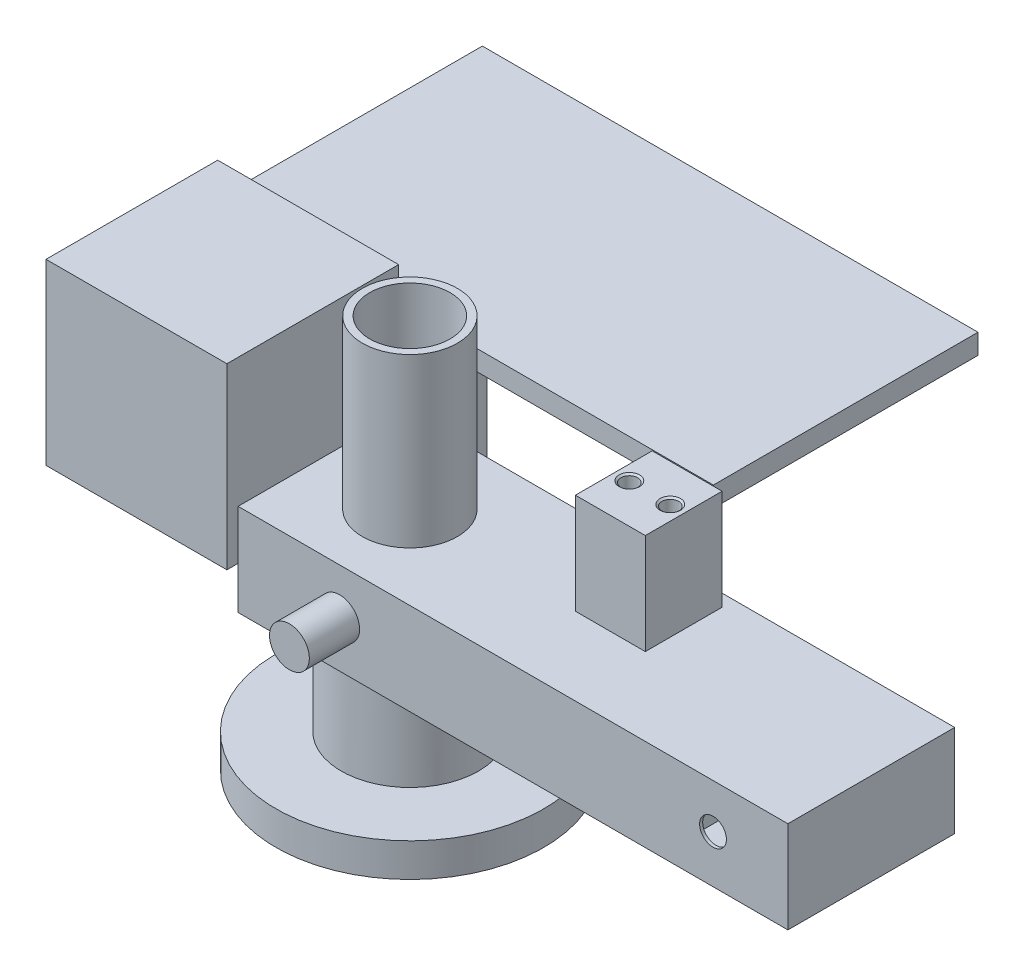
SolidWorks part; units mm, degrees
ref_plane "前基準面" through (0, 0, 0) normal (0, 0, 1) x (1, 0, 0)
ref_plane "上基準面" through (0, 0, 0) normal (0, 1, 0) x (1, 0, 0)
ref_plane "右基準面" through (0, 0, 0) normal (1, 0, 0) x (0, 0, -1)
sketch "草圖1" plane through (0, 0, 0) normal (0, 1, 0) x (1, 0, 0)
  line L1 (-30.3038, 12.448) -> (30.3038, 12.448)
  line L2 (-30.3038, 12.448) -> (-30.3038, -12.448)
  line L3 (-30.3038, -12.448) -> (30.3038, -12.448)
  line L4 (30.3038, 12.448) -> (30.3038, -12.448)
  line L5 (-30.3038, 12.448) -> (30.3038, -12.448) construction
  line L6 (-30.3038, -12.448) -> (30.3038, 12.448) construction
  point P0 (0, 0)
extrude "填料-伸長1" add sketch "草圖1" along normal blind 13.7304
sketch "草圖2" plane through (0, 0, 12.448) normal (0, 0, 1) x (1, 0, 0)
  line L6 (11.75, 12.75) -> (24.25, 12.75)
  line L7 (11.75, 12.75) -> (11.75, 2.25)
  line L8 (11.75, 2.25) -> (24.25, 2.25)
  line L9 (24.25, 12.75) -> (24.25, 2.25)
  line L10 (11.75, 12.75) -> (24.25, 2.25) construction
  line L11 (11.75, 2.25) -> (24.25, 12.75) construction
  point P10 (18, 7.5)
  dimension "D1" = 10.5
  dimension "D2" = 12.5
extrude "除料-伸長1" cut sketch "草圖2" against normal through all
sketch "草圖3" plane through (0, 0, 12.448) normal (0, 0, 1) x (1, 0, 0)
  line L0 (24.25, 2.25) -> (24.25, 12.75) construction
  line L1 (11.75, 12.75) -> (24.25, 12.75)
  line L2 (11.75, 12.75) -> (11.75, 2.25)
  line L3 (11.75, 2.25) -> (24.25, 2.25)
  line L4 (24.25, 12.75) -> (24.25, 2.25)
  line L5 (11.75, 12.75) -> (24.25, 2.25) construction
  line L6 (11.75, 2.25) -> (24.25, 12.75) construction
  line L7 (11.75, 2.25) -> (24.25, 2.25) construction
  point P0 (18, 7.5)
extrude "填料-伸長2" add sketch "草圖3" against normal blind 0.5
sketch "草圖4" plane through (0, 0, 11.948) normal (0, 0, -1) x (-1, 0, 0)
  circle A0 centre (-18, 7.5) radius 2
extrude "除料-伸長2" cut sketch "草圖4" against normal through all
sketch "草圖5" plane through (0, 0, 12.448) normal (0, 0, 1) x (1, 0, 0)
  circle A0 centre (-15.1519, 6.9) radius 2.975
extrude "填料-伸長3" add sketch "草圖5" along normal blind 7.5
sketch "草圖10" plane through (0, 13.7304, 0) normal (0, 1, 0) x (1, 0, 0)
  line L5 (8.4266, 10.6185) -> (18.8582, 10.6185)
  line L6 (8.4266, 10.6185) -> (8.4266, -0.8383)
  line L7 (8.4266, -0.8383) -> (18.8582, -0.8383)
  line L8 (18.8582, 10.6185) -> (18.8582, -0.8383)
  line L9 (8.4266, 10.6185) -> (18.8582, -0.8383) construction
  line L10 (8.4266, -0.8383) -> (18.8582, 10.6185) construction
  point P0 (13.6424, 4.8901)
extrude "填料-伸長4" add sketch "草圖10" along normal blind 15
sketch "草圖14" plane through (0, 0, 12.448) normal (0, 0, 1) x (1, 0, 0)
  circle A0 centre (18, 7.5) radius 2.8505
  circle A1 centre (18, 7.5) radius 2
extrude "填料-伸長5" add sketch "草圖14" along normal blind 1.5
sketch "草圖16" plane through (0, 0, 0) normal (0, -1, 0) x (1, 0, 0)
  circle A0 centre (-17.1174, 0) radius 5.5
  circle A1 centre (-17.1174, 0) radius 7.5
extrude "填料-伸長6" add sketch "草圖16" along normal blind 15
sketch "草圖17" plane through (0, -15, 0) normal (0, -1, 0) x (1, 0, 0)
  circle A0 centre (-17.1174, 0) radius 9.15
  circle A1 centre (-17.1174, 0) radius 17.05
extrude "填料-伸長7" add sketch "草圖17" along normal blind 5 separate body
sketch "草圖18" plane through (0, -15, 0) normal (0, 1, 0) x (1, 0, 0)
  circle A0 centre (-17.1174, 0) radius 10.2514
extrude "填料-伸長8" add sketch "草圖18" along normal blind 15
sketch "草圖19" plane through (0, -15, 0) normal (0, -1, 0) x (1, 0, 0)
  circle A0 centre (-17.1174, 0) radius 6
extrude "除料-伸長3" cut sketch "草圖19" against normal through all
sketch "草圖20" plane through (0, -20, 0) normal (0, -1, 0) x (1, 0, 0)
  line L1 (-27.7874, 1.565) -> (-27.7874, -1.565)
  line L2 (-27.7874, 1.565) -> (-26.1326, 1.565)
  line L3 (-27.7874, -1.565) -> (-26.1326, -1.565)
  line L4 (-26.1326, 1.565) -> (-26.1326, -1.565)
  circle A0 centre (-17.1174, 0) radius 9.15 construction
  point P7 (-27.7874, 0)
extrude "除料-伸長4" cut sketch "草圖20" against normal blind 15
sketch "草圖21" plane through (0, -15, 0) normal (0, -1, 0) x (1, 0, 0)
  line L0 (-26.1326, 1.565) -> (-25.7373, 1.565)
  line L1 (-26.1326, -1.565) -> (-25.7373, -1.565)
  line L2 (-25.7373, -1.565) -> (-25.7373, 1.565)
  line L3 (-26.1326, 1.565) -> (-26.1326, -1.565)
extrude "除料-伸長5" cut sketch "草圖21" against normal blind 10
sketch "草圖22" plane through (0, -15, 0) normal (0, 1, 0) x (1, 0, 0)
  circle A0 centre (-17.1174, 0) radius 19.9648
extrude "除料-伸長6" cut sketch "草圖22" against normal blind 10
sketch "草圖47" plane through (0, -15, 0) normal (0, -1, 0) x (1, 0, 0)
  circle A0 centre (-17.1174, 0) radius 20
extrude "填料-伸長16" add sketch "草圖47" along normal blind 5
sketch "草圖48" plane through (0, -15, 0) normal (0, 1, 0) x (1, 0, 0)
  circle A0 centre (-17.1174, 0) radius 6
extrude "除料-伸長21" cut sketch "草圖48" against normal blind 5
sketch "草圖49" plane through (0, -20, 0) normal (0, -1, 0) x (1, 0, 0)
  circle A0 centre (-17.1174, 0) radius 17.3
  circle A1 centre (-17.1174, 0) radius 14.8
extrude "除料-伸長22" cut sketch "草圖49" against normal blind 3
sketch "草圖50" plane through (0, -20, 0) normal (0, -1, 0) x (1, 0, 0)
  circle A0 centre (-17.1174, 0) radius 18.5909
  arc A1 (-2.1064, 10.9677) -> (0.2479, 6.6384) centre (-17.1174, 0) cw
  circle A2 centre (-17.1174, 0) radius 8.4841
sketch "草圖51" plane through (0, -20, 0) normal (0, -1, 0) x (1, 0, 0)
  line L0 (-3.1487, 10.2061) -> (-2.1064, 10.9677)
  line L1 (-0.958, 6.1775) -> (0.2479, 6.6384)
  line L2 (-15.2631, -17.2003) -> (-15.1247, -18.4838)
  line L3 (-19.8473, -17.0833) -> (-20.051, -18.358)
  line L4 (-32.9405, 6.9942) -> (-34.1213, 7.5161)
  line L5 (-30.547, 10.9058) -> (-31.5491, 11.7196)
  arc A0 (-3.1487, 10.2061) -> (-0.958, 6.1775) centre (-17.1174, 0) cw
  circle A1 centre (-17.1174, 0) radius 17.3 construction
  arc A2 (-15.1247, -18.4838) -> (-20.051, -18.358) centre (-17.1174, 0) cw
  arc A3 (-2.1064, 10.9677) -> (0.2479, 6.6384) centre (-17.1174, 0) cw
  arc A4 (-15.2631, -17.2003) -> (-19.8473, -17.0833) centre (-17.1174, 0) cw
  arc A5 (-34.1213, 7.5161) -> (-31.5491, 11.7196) centre (-17.1174, 0) cw
  arc A6 (-32.9405, 6.9942) -> (-30.547, 10.9058) centre (-17.1174, 0) cw
  point P23 (-17.1174, 0)
  dimension "D1" = 3
extrude "除料-伸長23" cut sketch "草圖51" against normal blind 3
sketch "草圖52" plane through (0, -17, 0) normal (0, -1, 0) x (1, 0, 0)
  circle A0 centre (-17.1174, 0) radius 18.5909
extrude "除料-伸長24" cut sketch "草圖52" along normal blind 2.3
sketch "草圖43" plane through (0, 0, 0) normal (0, -1, 0) x (1, 0, 0)
  line L0 (-30.3038, 14.126) -> (-30.3038, -14.126)
  line L1 (-57.3038, -14.126) -> (-57.3038, 14.126)
  line L2 (-30.3038, -14.126) -> (-57.3038, -14.126)
  line L3 (-57.3038, 14.126) -> (-30.3038, 14.126)
  line L6 (-55.9538, 12.15) -> (-31.6538, 12.15)
  line L7 (-55.9538, 12.15) -> (-55.9538, -12.15)
  line L8 (-55.9538, -12.15) -> (-31.6538, -12.15)
  line L9 (-31.6538, 12.15) -> (-31.6538, -12.15)
  line L10 (-55.9538, 12.15) -> (-31.6538, -12.15) construction
  line L11 (-55.9538, -12.15) -> (-31.6538, 12.15) construction
  point P3 (-30.3038, 0)
  point P7 (-43.8038, 0)
  dimension "D1" = 27
  dimension "D2" = 24.3
  dimension "D3" = 24.3
extrude "填料-伸長14" add sketch "草圖43" against normal blind 10
sketch "草圖53" plane through (0, -20, 0) normal (0, -1, 0) x (1, 0, 0)
  line L0 (-21.4684, 18.0746) -> (-18.5217, 5.8334)
  line L1 (-12.8881, 18.1034) -> (-15.7525, 5.8427)
  line L2 (0.7111, -5.2692) -> (-11.3635, -1.7006)
  line L3 (-3.5541, -12.7145) -> (-12.74, -4.1034)
  line L4 (-30.595, -12.8054) -> (-21.4672, -4.1328)
  line L5 (-34.9102, -5.389) -> (-22.8598, -1.7392)
  circle A1 centre (-17.1174, 0) radius 18.5909 construction
  circle A2 centre (-17.1174, 0) radius 6 construction
  arc A3 (-15.7525, 5.8427) -> (-18.5217, 5.8334) centre (-17.1174, 0) ccw
  arc A4 (-21.4684, 18.0746) -> (-12.8881, 18.1034) centre (-17.1174, 0) cw
  arc A5 (0.7111, -5.2692) -> (-3.5541, -12.7145) centre (-17.1174, 0) cw
  arc A6 (-12.74, -4.1034) -> (-11.3635, -1.7006) centre (-17.1174, 0) ccw
  arc A7 (-30.595, -12.8054) -> (-34.9102, -5.389) centre (-17.1174, 0) cw
  arc A8 (-22.8598, -1.7392) -> (-21.4672, -4.1328) centre (-17.1174, 0) ccw
  point P20 (-17.1174, 0)
  dimension "D1" = 3
extrude "填料-伸長17" add sketch "草圖53" against normal blind 5
sketch "草圖54" plane through (0, -20, 0) normal (0, -1, 0) x (1, 0, 0)
  circle A0 centre (-17.1174, 0) radius 14.8
  circle A1 centre (-17.1174, 0) radius 6
extrude "填料-伸長18" add sketch "草圖54" against normal blind 5
sketch "草圖56" plane through (30.3038, 0, 0) normal (1, 0, 0) x (0, 0, -1)
  line L0 (14.126, 10) -> (14.126, 0)
  line L1 (14.126, 0) -> (12.448, 0)
  line L2 (12.448, 0) -> (12.448, 10)
  line L3 (14.126, 10) -> (12.448, 10) construction
  line L4 (12.448, 10) -> (14.126, 10)
extrude "填料-伸長19" add sketch "草圖56" against normal blind 80
sketch "草圖57" plane through (0, 0, -12.448) normal (0, 0, -1) x (-1, 0, 0)
  line L0 (-24.25, 12.75) -> (-11.75, 12.75)
  line L1 (-11.75, 12.75) -> (-11.75, 0.75)
  line L2 (-24.25, 12.75) -> (-24.25, 0.75)
  line L3 (-24.25, 0.75) -> (-11.75, 0.75)
extrude "除料-伸長28" cut sketch "草圖57" along normal blind 80
sketch "草圖58" plane through (30.3038, 0, 0) normal (1, 0, 0) x (0, 0, -1)
  line L0 (12.448, 10) -> (14.126, 10)
  line L1 (14.126, 10) -> (14.126, 0)
  line L2 (14.126, 0) -> (12.448, 0)
  line L3 (12.448, 0) -> (12.448, 10)
extrude "除料-伸長29" cut sketch "草圖58" against normal blind 18.5
sketch "草圖59" plane through (0, 0, -14.126) normal (0, 0, -1) x (-1, 0, 0)
  line L0 (-11.75, 10) -> (-11.75, 43)
  line L1 (-11.75, 10) -> (-6.75, 10)
  line L2 (57.3038, 10) -> (-11.75, 10) construction
  line L3 (-6.75, 10) -> (-6.75, 43)
  line L4 (-6.75, 43) -> (-11.75, 43)
  line L5 (57.3038, 10) -> (57.3038, 43)
  line L6 (57.3038, 43) -> (52.3038, 43)
  line L7 (52.3038, 43) -> (52.3038, 0)
  line L8 (57.3038, 0) -> (-11.8038, 0) construction
  line L9 (52.3038, 0) -> (57.3038, 0)
  line L10 (19.7432, 0) -> (19.7432, 43)
  line L11 (19.7432, 43) -> (24.7432, 43)
  line L12 (24.7432, 43) -> (24.7432, 0)
  line L13 (24.7432, 0) -> (19.7432, 0)
  line M14 (57.3038, 10) -> (-11.75, 10)
  dimension "D1" = 5
  dimension "D2" = 5
  dimension "D3" = 5
extrude "填料-伸長21" add sketch "草圖59" against normal blind 2.621 contours L3 L4 L0 M14 | L12 L11 L10 M14 | L6 L7 L5 M14
sketch "草圖60" plane through (-57.3038, 0, 0) normal (-1, 0, 0) x (0, 0, 1)
  line L0 (-14.126, 43) -> (-39.126, 43)
  line L1 (-39.126, 43) -> (-39.126, 38.9382)
  line L4 (-39.126, 38.9382) -> (-14.126, 38.9382)
  line L5 (-14.126, 38.9382) -> (-14.126, 43)
  line L10 (-14.126, 0) -> (14.126, 0)
  line L11 (14.126, 0) -> (14.126, 10)
  line L12 (14.126, 10) -> (-11.5051, 10)
  line L15 (-14.126, 43) -> (-14.126, 0)
  line L16 (-14.126, 0) -> (14.126, 0)
  line L17 (14.126, 0) -> (14.126, 10)
  line L18 (14.126, 10) -> (-11.5051, 10)
  line L21 (-14.126, 43) -> (-14.126, 0)
  line L22 (-11.5051, 10) -> (-11.5051, 43)
  line L23 (-11.5051, 10) -> (-11.5051, 43)
  line L24 (-11.5051, 43) -> (-14.126, 43)
  line M12 (-14.126, 43) -> (-14.126, 0)
  dimension "D1" = 0
extrude "填料-伸長22" add sketch "草圖60" against normal blind 69.2 contours L1 L4 L0 M12
sketch "草圖61" plane through (0, 43, 0) normal (0, 1, 0) x (1, 0, 0)
  line L0 (6.75, 14.126) -> (6.75, 34.126)
  line L1 (-19.7432, 14.126) -> (-19.7432, 34.126)
  line L2 (-19.7432, 34.126) -> (6.75, 34.126)
  line L3 (-24.7432, 14.126) -> (-24.7432, 34.126)
  line L4 (-52.3038, 14.126) -> (-52.3038, 34.126)
  line L5 (-52.3038, 34.126) -> (-24.7432, 34.126)
  line L6 (-52.3038, 14.126) -> (-24.7432, 14.126)
  line L7 (-19.7432, 14.126) -> (6.75, 14.126)
extrude "除料-伸長30" cut sketch "草圖61" against normal blind 5.2
sketch "草圖62" plane through (0, 38.9382, 0) normal (0, -1, 0) x (1, 0, 0)
  line L0 (-57.3038, -39.126) -> (11.8962, -39.126)
  line L1 (-52.3038, -34.126) -> (11.8962, -34.126)
  line L2 (11.8962, -39.126) -> (11.8962, -14.126) construction
  line L3 (11.8962, -34.126) -> (11.8962, -39.126)
  line L4 (-57.3038, -39.126) -> (-57.3038, -34.126)
  line L5 (-57.3038, -39.126) -> (-57.3038, -14.126) construction
  line L6 (-57.3038, -34.126) -> (-52.3038, -34.126)
sketch "草圖68" plane through (0, 0, -34.126) normal (0, 0, 1) x (1, 0, 0)
  line L0 (-65.7613, 43) -> (20.2387, 43)
  line L2 (20.2387, 43) -> (20.2387, 28)
  line L3 (20.2387, 28) -> (-65.7613, 28)
  line L4 (-65.7613, 28) -> (-65.7613, 43)
  point P3 (-22.7613, 43)
  dimension "D1" = 86
extrude "填料-伸長25" add sketch "草圖68" against normal blind 3
sketch "草圖69" plane through (0, 0, -39.126) normal (0, 0, -1) x (-1, 0, 0)
  line L0 (-11.8962, 43) -> (-11.8962, 38.9382)
  line L1 (-11.8962, 38.9382) -> (57.3038, 38.9382)
  line L2 (57.3038, 38.9382) -> (57.3038, 43)
  line L3 (57.3038, 43) -> (-11.8962, 43)
extrude "除料-伸長34" cut sketch "草圖69" against normal blind 2
sketch "草圖70" plane through (20.2387, 0, 0) normal (1, 0, 0) x (0, 0, -1)
  line L0 (37.126, 28) -> (37.126, 43)
  line L1 (37.126, 43) -> (14.126, 43)
  line L2 (14.126, 43) -> (14.126, 28)
  line L3 (14.126, 38.9382) -> (14.126, 0.75) construction
  line L4 (14.126, 28) -> (37.126, 28)
extrude "填料-伸長27" add sketch "草圖70" along normal blind 2
sketch "草圖71" plane through (-65.7613, 0, 0) normal (-1, 0, 0) x (0, 0, 1)
  line L0 (-37.126, 28) -> (-14.126, 28)
  line L1 (-14.126, 28) -> (-14.126, 43)
  line L2 (-11.5051, 43) -> (-34.126, 43) construction
  line L3 (-14.126, 43) -> (-14.126, 28) construction
  line L4 (-14.126, 43) -> (-37.126, 43)
  line L5 (-37.126, 43) -> (-37.126, 28)
extrude "填料-伸長28" add sketch "草圖71" along normal blind 2
sketch "草圖72" plane through (-57.3038, 0, 0) normal (-1, 0, 0) x (0, 0, 1)
  line L0 (-14.126, 43) -> (-11.5051, 43)
  line L1 (-11.5051, 43) -> (-11.5051, 27.998)
  line L2 (-11.5051, 10) -> (-11.5051, 43) construction
  line L3 (-11.5051, 27.998) -> (-14.126, 28)
  line L4 (-14.126, 28) -> (-14.126, 43)
extrude "填料-伸長29" add sketch "草圖72" along normal blind 10.5
sketch "草圖73" plane through (11.75, 0, 0) normal (1, 0, 0) x (0, 0, -1)
  line L0 (11.5051, 27.998) -> (14.126, 28)
  line L1 (14.126, 28) -> (14.126, 43)
  line L2 (14.126, 43) -> (11.5051, 43)
  line L3 (11.5051, 43) -> (11.5051, 27.998)
extrude "填料-伸長30" add sketch "草圖73" along normal blind 10.5
sketch "草圖74" plane through (0, 10, 0) normal (0, -1, 0) x (1, 0, 0)
  line L0 (-52.3038, -11.5051) -> (-55.9538, -11.5051)
  line L1 (-55.9538, -11.5051) -> (-55.9538, -12.15)
  line L2 (-55.9538, -12.15) -> (-52.3038, -12.15)
  line L3 (-52.3038, -12.15) -> (-52.3038, -11.5051)
extrude "除料-伸長35" cut sketch "草圖74" against normal through all
sketch "草圖76" plane through (13.6424, 28.7304, -0.3792) normal (0, 1, 0) x (1, 0, 0)
  line L0 (-3.0568, 4.6706) -> (3.0568, 4.6706)
  point P1 (3.0568, 4.6706)
  point P2 (-3.0568, 4.6706)
  point P3 (0, 4.6706)
hole_wizard "M3 螺紋孔1" positions "草圖80" profile "草圖82" tap size "M3" standard "ISO"
sketch "草圖80" plane through (0, 28.7304, 0) normal (0, 1, 0) x (1, 0, 0)
  point P0 (10.5856, 5.0498)
  point P3 (16.6992, 5.0498)
sketch "草圖82" plane through (10.5856, 28.7304, -5.0498) normal (1, 0, 0) x (0, 0, 1)
  line L0 (0, 0) -> (0, 15.7511)
  line L1 (0, 15.7511) -> (1.25, 15)
  line L2 (1.25, 15) -> (1.25, 0.2308)
  line L3 (1.25, 0.2308) -> (1.525, 0)
  line L5 (1.525, 0) -> (0, 0)
  line L6 (-1.25, 0.2308) -> (-1.525, 0) construction
  line L10 (0, 15.7511) -> (-1.25, 15) construction
  line L11 (0, -6.35) -> (0, 107.95) construction
  dimension "螺孔鑽直徑" = 2.5
  dimension "螺孔鑽深度" = 15
  dimension "近端錐孔直徑" = 3.05
  dimension "近端錐孔角度" = 100
  dimension "導頭角度" = 118
cosmetic thread "鑽孔螺紋1" parameters "D1"=2.7, "D2"=3
cosmetic thread "鑽孔螺紋2" parameters "D1"=2.7, "D2"=3
sketch "草圖83" plane through (-67.7613, 0, 0) normal (-1, 0, 0) x (0, 0, 1)
  line L0 (-37.126, 43) -> (-37.126, 28)
  line L1 (-37.126, 28) -> (-11.5051, 27.998)
  line L2 (-11.5051, 27.998) -> (-11.5051, 43)
  line L3 (-11.5051, 43) -> (-37.126, 43)
extrude "除料-伸長36" cut sketch "草圖83" against normal through all
sketch "草圖84" plane through (-67.8038, 0, 0) normal (-1, 0, 0) x (0, 0, 1)
  line L0 (-18.2068, 44.5992) -> (-5.6417, 43.5029)
  line L1 (-5.6417, 43.5029) -> (-11.5051, 27.998)
  line L2 (-11.5051, 27.998) -> (-14.126, 27.9982)
  line L3 (-14.126, 27.9982) -> (-18.2068, 44.5992)
extrude "除料-伸長37" cut sketch "草圖84" against normal through all
sketch "草圖85" plane through (0, 27.9971, 0.0022) normal (0, 1, 0.0001) x (1, 0, 0)
  line L0 (11.75, 11.5062) -> (-57.3038, 11.5059)
  line L1 (-57.3038, 11.5059) -> (-57.3038, 46.7116)
  line L2 (-57.3038, 46.7116) -> (11.7499, 46.7116)
  line L3 (11.7499, 46.7116) -> (11.75, 11.5062)
sketch "草圖87" plane through (0, 13.7304, 0) normal (0, 1, 0) x (1, 0, 0)
  circle A0 centre (-17.1174, 0) radius 7.0952
  circle A1 centre (-17.1174, 0) radius 6
extrude "填料-伸長32" add sketch "草圖87" along normal blind 25
sketch "草圖88" plane through (0, 27.9971, 0.0022) normal (0, 1, 0.0001) x (1, 0, 0)
  line L0 (-57.3038, 11.5059) -> (16.6752, 11.5059)
  line L1 (16.6752, 11.5059) -> (16.6752, 51.0037)
  line L2 (16.6752, 51.0037) -> (-57.3038, 51.0037)
  line L3 (-57.3038, 51.0037) -> (-57.3038, 11.5059)
extrude "填料-伸長33" add sketch "草圖88" against normal blind 3
sketch "草圖89" plane through (11.75, 0, 0) normal (1, 0, 0) x (0, 0, -1)
  line L0 (-12.448, 13.7304) -> (12.448, 13.7304)
  line L1 (12.448, 13.7304) -> (12.448, 0)
  line L2 (12.448, 0) -> (-12.448, 0)
  line L3 (-12.448, 0) -> (-12.448, 13.7304)
extrude "填料-伸長34" add sketch "草圖89" along normal blind 40
sketch "草圖90" plane through (0, 0, 12.448) normal (0, 0, 1) x (1, 0, 0)
  circle A0 centre (18, 7.5) radius 3.7574
extrude "除料-伸長38" cut sketch "草圖90" along normal through all
sketch "草圖91" plane through (0, 0, -12.448) normal (0, 0, -1) x (-1, 0, 0)
  line L0 (-46.8224, 12.3625) -> (-46.8224, 1.8625)
  line L1 (-46.8224, 1.8625) -> (-34.3224, 1.8625)
  line L2 (-46.8224, 12.3625) -> (-34.3224, 12.3625)
  line L3 (-34.3224, 12.3625) -> (-34.3224, 1.8625)
extrude "除料-伸長39" cut sketch "草圖91" against normal through all
sketch "草圖92" plane through (34.3224, 0, 0) normal (1, 0, 0) x (0, 0, -1)
  line L0 (-12.448, 12.3625) -> (-11.9894, 12.3625)
  line L1 (-11.9894, 12.3625) -> (-11.9894, 1.2188)
  line L2 (-11.9894, 1.2188) -> (-12.448, 1.2188)
  line L3 (-12.448, 10) -> (-12.448, 0) construction
  line L4 (-12.448, 1.2188) -> (-12.448, 12.3625)
extrude "填料-伸長35" add sketch "草圖92" along normal blind 15
sketch "草圖93" plane through (0, 0, 11.9894) normal (0, 0, -1) x (-1, 0, 0)
  circle A0 centre (-40.5724, 7.1125) radius 2
extrude "除料-伸長40" cut sketch "草圖93" against normal through all
sketch "草圖94" plane through (0, 0, 12.448) normal (0, 0, 1) x (1, 0, 0)
  circle A0 centre (40.5724, 7.1125) radius 23
  dimension "D1" = 46
sketch "草圖95" plane through (0, 10, 0) normal (0, 1, 0) x (1, 0, 0)
  line L0 (-57.3038, 11.5037) -> (-57.3038, -14.126)
  line L1 (-57.3038, -14.126) -> (-30.3038, -14.126)
  line L2 (-30.3038, -14.126) -> (-30.3038, 11.5038)
  line L3 (11.75, 11.504) -> (-57.3038, 11.5037) construction
  line L4 (-30.3038, 11.5038) -> (-57.3038, 11.5037)
  line L5 (-55.9538, 11.5051) -> (-55.9538, -12.15)
  line L6 (-55.9538, -12.15) -> (-31.6538, -12.15)
  line L7 (-31.6538, -12.15) -> (-31.6538, 12.15)
  line M3 (-31.6538, 12.15) -> (-31.6538, -12.15)
  line M4 (-31.6538, -12.15) -> (-55.9538, -12.15)
  line M5 (-55.9538, -12.15) -> (-55.9538, 11.5051)
  line M7 (-57.3038, 11.5051) -> (-57.3038, -14.126)
  line M8 (-57.3038, -14.126) -> (-30.3038, -14.126)
  line M9 (-30.3038, -14.126) -> (-30.3038, -12.448)
  line M10 (-30.3038, -12.448) -> (-30.3038, 12.448)
extrude "填料-伸長36" add sketch "草圖95" along normal blind 20 contours L4 M10 M3 M4 M5 M7 M8 M9
sketch "草圖96" plane through (0, 0, 14.126) normal (0, 0, 1) x (1, 0, 0)
  line L0 (-57.3038, 0) -> (-30.3038, 0)
  line L1 (-30.3038, 0) -> (-30.3038, 6.3579)
  line L2 (-30.3038, 30) -> (-30.3038, 0) construction
  line L3 (-30.3038, 6.3579) -> (-57.3038, 6.3579)
  line L4 (-57.3038, 30) -> (-57.3038, 0) construction
  line L5 (-57.3038, 6.3579) -> (-57.3038, 0)
extrude "除料-伸長41" cut sketch "草圖96" against normal through all
sketch "草圖97" plane through (0, 30, 0) normal (0, 1, 0) x (1, 0, 0)
  line L0 (-57.3038, 11.5037) -> (-30.3038, 11.5037)
  line L1 (-30.3038, 11.5037) -> (-30.3038, -14.126)
  line L2 (-30.3038, -14.126) -> (-57.3038, -14.126)
  line L3 (-57.3038, -14.126) -> (-57.3038, 11.5037)
extrude "填料-伸長37" add sketch "草圖97" along normal blind 3
